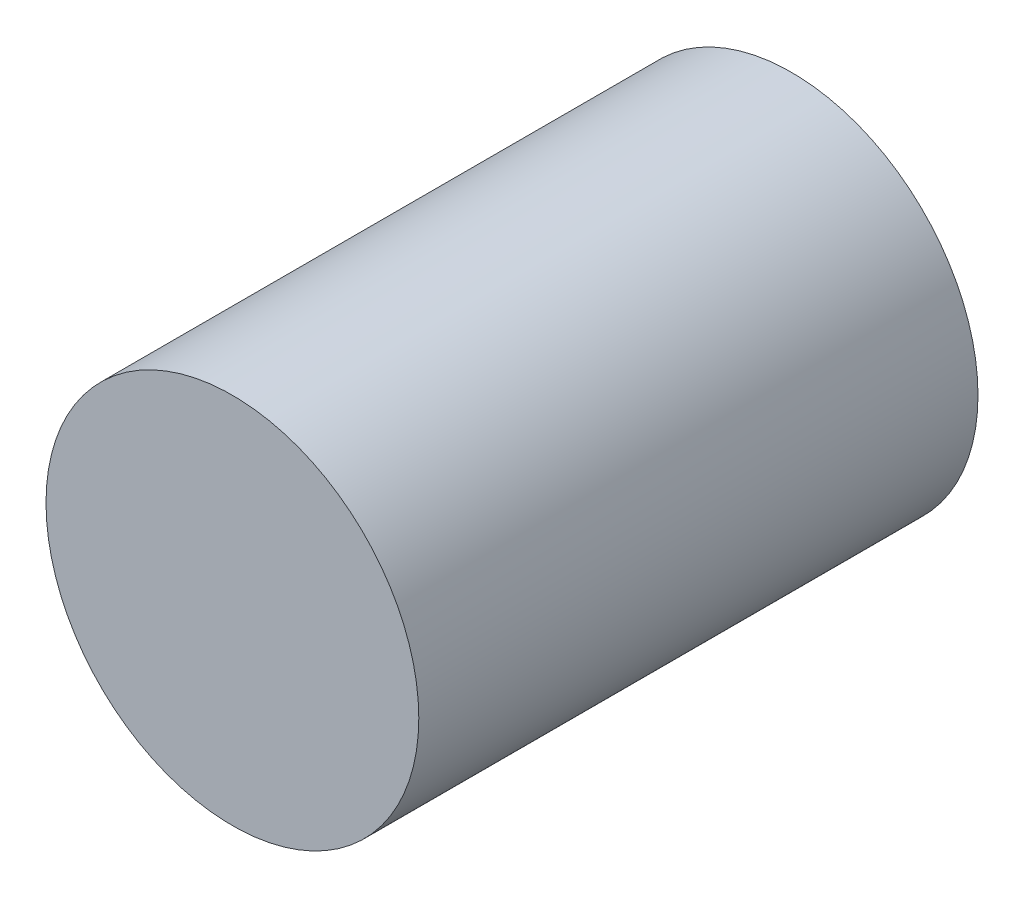
SolidWorks part; units mm, degrees
material "Acier allié"
ref_plane "Front Plane" through (0, 0, 0) normal (0, 0, 1) x (1, 0, 0)
ref_plane "Top Plane" through (0, 0, 0) normal (0, 1, 0) x (1, 0, 0)
ref_plane "Right Plane" through (0, 0, 0) normal (1, 0, 0) x (0, 0, -1)
sketch "Esquisse1" plane through (0, 0, 0) normal (0, 0, 1) x (1, 0, 0)
  circle A0 centre (0, 0) radius 10
  dimension "D1" = 20
extrude "Boss.-Extru.1" add sketch "Esquisse1" along normal mid plane 30
